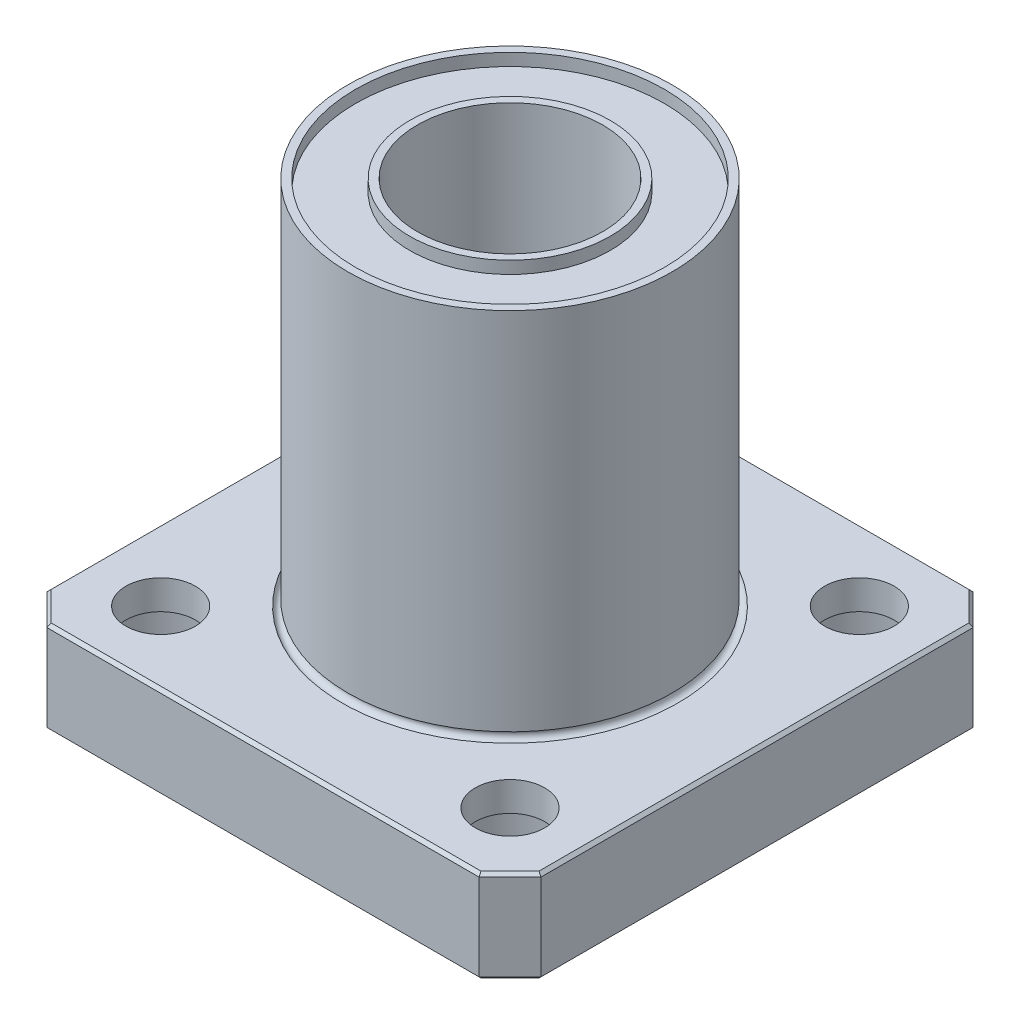
SolidWorks part; units mm, degrees
ref_plane "Front Plane" through (0, 0, 0) normal (0, 0, 1) x (1, 0, 0)
ref_plane "Top Plane" through (0, 0, 0) normal (0, 1, 0) x (1, 0, 0)
ref_plane "Right Plane" through (0, 0, 0) normal (1, 0, 0) x (0, 0, -1)
sketch "Sketch5" plane through (0, 0, 0) normal (1, 0, 0) x (0, 0, -1)
  line L0 (0, 0) -> (0, 30) construction
  line L1 (6.5, 30) -> (6, 30)
  line L2 (10.5, 0) -> (10.5, 30)
  line L3 (10.5, 30) -> (10, 30)
  line L4 (10, 30) -> (10, 29.2)
  line L5 (10, 29.2) -> (6.5, 29.2)
  line L6 (6.5, 29.2) -> (6.5, 30)
  line L7 (10.5, 7.7505) -> (-10.5, 7.7505) construction
  line L9 (6, 30) -> (6, 0)
  line L10 (6, 0) -> (6.5, 0)
  line L11 (6.5, 0) -> (6.5, 0.8)
  line L12 (6.5, 0.8) -> (10, 0.8)
  line L13 (10, 0.8) -> (10, 0)
  line L14 (10, 0) -> (10.5, 0)
  line L15 (-10.5, 7.7505) -> (-10.5, 0) construction
  line L17 (-6, 0) -> (-6, 10.4788) construction
  line L18 (-6, 10.4788) -> (6, 10.4788) construction
  point P2 (0, 10.4788)
  point P18 (0, 7.7505)
  dimension "D1" = 12
  dimension "D2" = 0.5
  dimension "D3" = 0.8
  dimension "D4" = 21
  dimension "D5" = 30
revolve "Bearing Body" add sketch "Sketch5" angle 360 about L0
sketch "Sketch8" plane through (0, 0, 0) normal (0, 1, 0) x (1, 0, 0)
  line L0 (0, -10.5) -> (0, -16) construction
  line L1 (16, 16) -> (-16, 16) construction
  line L2 (16, 16) -> (16, -16) construction
  line L3 (16, -16) -> (-16, -16) construction
  line L4 (-16, 16) -> (-16, -16) construction
  line L5 (16, 16) -> (-16, -16) construction
  line L6 (16, -16) -> (-16, 16) construction
  line L7 (0, -16) -> (-14, -16)
  line L8 (-14, -16) -> (-16, -14)
  line L9 (-16, -14) -> (-16, 0)
  line L10 (-16, 0) -> (-10.5, 0) construction
  line L11 (0, 0) -> (0.0644, 0.2794) construction
  line L12 (-16, -14) -> (-16, -16) construction
  line L13 (-16, -16) -> (-14, -16) construction
  line L14 (-16, 0) -> (-16, 14)
  line L15 (-16, 14) -> (-14, 16)
  line L16 (-14, 16) -> (0, 16)
  line L17 (-10.5, 0) -> (-16, 0) construction
  line L18 (0, 16) -> (0, 10.5) construction
  line L19 (0, 0) -> (0.2794, -0.0644) construction
  line L20 (0, 16) -> (14, 16)
  line L21 (14, 16) -> (16, 14)
  line L22 (16, 14) -> (16, 0)
  line L23 (0, 10.5) -> (0, 16) construction
  line L24 (16, 0) -> (10.5, 0) construction
  line L25 (0, 0) -> (-0.0644, -0.2794) construction
  line L26 (16, 0) -> (16, -14)
  line L27 (16, -14) -> (14, -16)
  line L28 (14, -16) -> (0, -16)
  line L29 (10.5, 0) -> (16, 0) construction
  line L30 (0, -16) -> (0, -10.5) construction
  line L31 (0, 0) -> (-0.2794, 0.0644) construction
  circle A0 centre (0, 0) radius 10.5 construction
  arc A1 (-10.5, 0) -> (0, -10.5) centre (0, 0) ccw
  arc A2 (0, 10.5) -> (-10.5, 0) centre (0, 0) ccw
  arc A3 (10.5, 0) -> (0, 10.5) centre (0, 0) ccw
  arc A4 (0, -10.5) -> (10.5, 0) centre (0, 0) ccw
  point P38 (0, 0)
  dimension "D1" = 32
  dimension "D2" = 2
  dimension "D3" = 4
extrude "Flange" add sketch "Sketch8" along normal blind 6
sketch "Sketch9" plane through (0, 0, 0) normal (0, -1, 0) x (-1, 0, 0)
  line L0 (0, 0) -> (16, -16) construction
  line L1 (0, 0) -> (50000, 0) construction
  circle A0 centre (0, 0) radius 16 construction
  circle A1 centre (11.3137, -11.3137) radius 4
  circle A2 centre (-11.3137, -11.3137) radius 4
  circle A3 centre (-11.3137, 11.3137) radius 4
  circle A4 centre (11.3137, 11.3137) radius 4
  point P16 (0, 0)
  dimension "D1" = 32
  dimension "D2" = 8
  dimension "D4" = 45
  dimension "D3" = 4
extrude "Counterbore" cut sketch "Sketch9" against normal blind 4.1
sketch "Sketch10" plane through (0, 4.1, 0) normal (0, -1, 0) x (-1, 0, 0)
  circle A0 centre (11.3137, 11.3137) radius 2.25
  circle A1 centre (11.3137, -11.3137) radius 2.25
  circle A2 centre (-11.3137, -11.3137) radius 2.25
  circle A3 centre (-11.3137, 11.3137) radius 2.25
  point P12 (0, 0)
  dimension "D1" = 4
extrude "Mounting Holes" cut sketch "Sketch10" against normal through all
sketch "Sketch11" plane through (0, 0, 0) normal (1, 0, 0) x (0, 0, -1)
  line L0 (0, 0) -> (0, 50000) construction
  line L3 (-16, 6) -> (16, 6) construction
  line L4 (10.5, 6) -> (-10.5, 6) construction
  line L5 (-10.5, 30) -> (-10.5, 6) construction
  line L6 (-10.5, 30) -> (-10.5, 6) construction
  line L8 (-14, 6) -> (14, 6) construction
  line L9 (-14, 6) -> (14, 6) construction
  circle A0 centre (-10.5, 6) radius 0.375
  dimension "D3" = 0.75
revolve "Relief" cut sketch "Sketch11" angle 360 about L0
chamfer "Chamfer1" distance 0.2 angle 45 16 edges at (15, 0, -15) (15, 6, -15) (16, 0, 0) (16, 6, 0) (15, 0, 15) (15, 6, 15) (0, 0, 16) (0, 6, 16) (-15, 0, 15) (-15, 6, 15) (-16, 0, 0) (-16, 6, 0) (0, 0, -16) (0, 6, -16) (-15, 0, -15) (-15, 6, -15)
